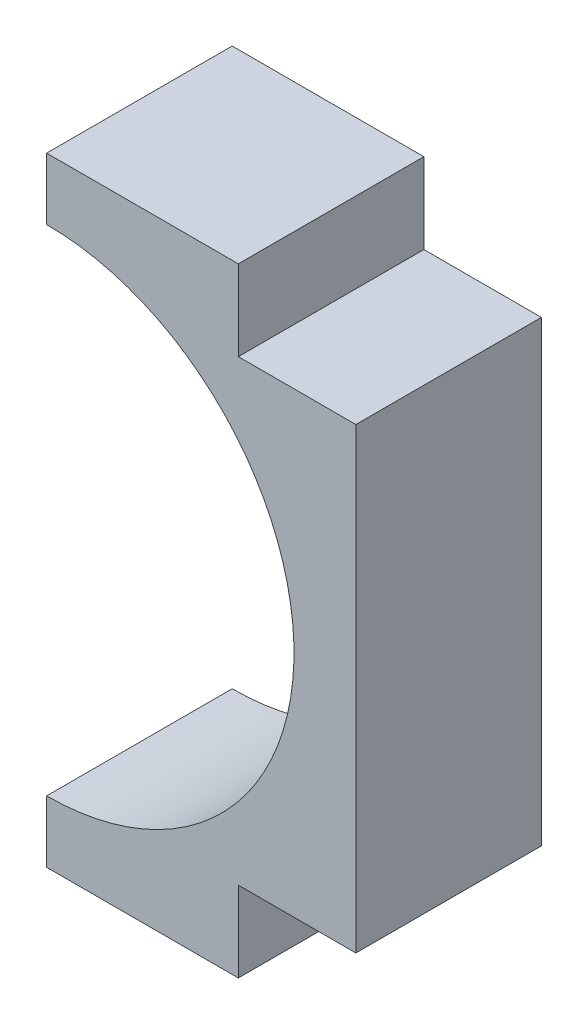
SolidWorks part; units mm, degrees
ref_plane "Спереди" through (0, 0, 0) normal (0, 0, 1) x (1, 0, 0)
ref_plane "Сверху" through (0, 0, 0) normal (0, 1, 0) x (1, 0, 0)
ref_plane "Справа" through (0, 0, 0) normal (1, 0, 0) x (0, 0, -1)
other "Configuration Table"
sketch "Эскиз1" plane through (0, 0, 0) normal (0, 0, 1) x (1, 0, 0)
  line L1 (0, 50) -> (50, 50)
  line L2 (0, 50) -> (0, -50)
  line L3 (0, -50) -> (50, -50)
  line L4 (50, 50) -> (50, -50)
  circle A0 centre (0, 0) radius 40
  point P3 (0, -40)
  point P4 (40, 0)
  point P9 (0, 40)
  dimension "D1" = 80
  dimension "D3" = 10
  dimension "D4" = 10
  dimension "D2" = 10
extrude "Бобышка-Вытянуть1" add sketch "Эскиз1" along normal blind 30 contours A0 L2 L3 L4 L1
chamfer "Фаска1" [suppressed] distance 20 angle 45
fillet "Скругление1" [suppressed] radius 2
sketch "Эскиз2" plane through (0, 0, 30) normal (0, 0, 1) x (1, 0, 0)
  line L1 (50, 50) -> (31, 50)
  line L2 (50, 50) -> (50, 37)
  line L3 (50, 37) -> (31, 37)
  line L4 (31, 50) -> (31, 37)
  dimension "D1" = 13
  dimension "D2" = 19
extrude "Вырез-Вытянуть1" cut sketch "Эскиз2" against normal through all
mirror "Зеркальное отражение1" about plane through (0, 0, 0) normal (0, 1, 0) of "Вырез-Вытянуть1"
